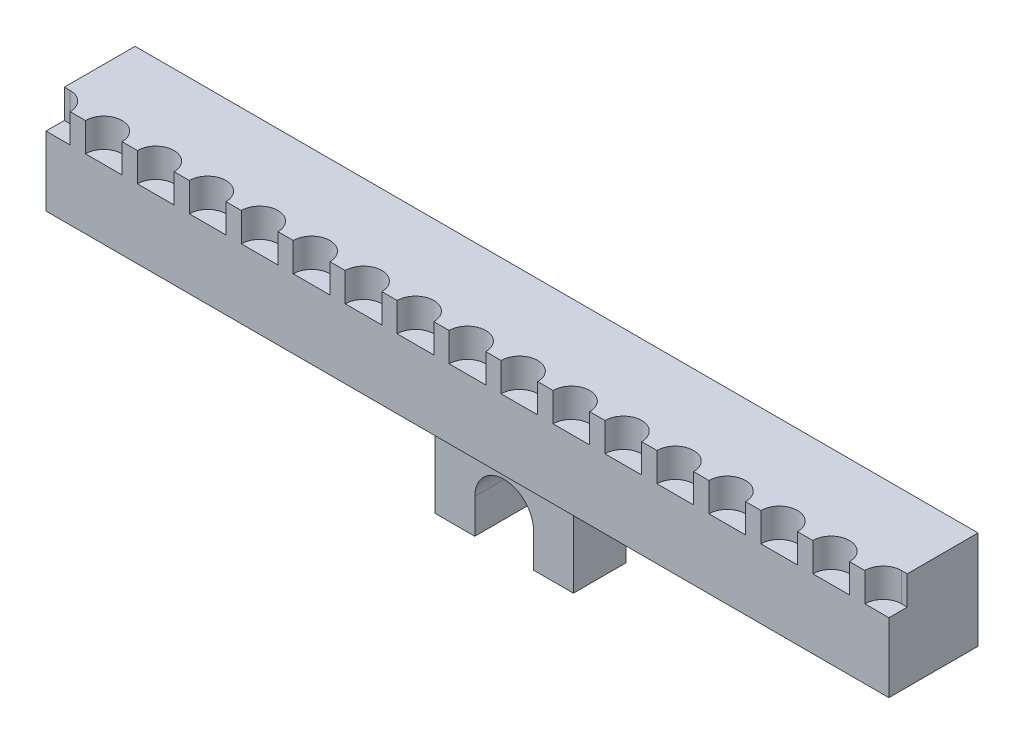
SolidWorks part; units mm, degrees
material "6061-T6 (SS)"
ref_plane "Front" through (0, 0, 0) normal (0, 0, 1) x (1, 0, 0)
ref_plane "Top" through (0, 0, 0) normal (0, 1, 0) x (1, 0, 0)
ref_plane "Right" through (0, 0, 0) normal (1, 0, 0) x (0, 0, -1)
sketch "Sketch1" plane through (0, 0, 0) normal (0, 1, 0) x (1, 0, 0)
  line L1 (-36.5, -7.215) -> (36.5, -7.215)
  line L2 (-36.5, -7.215) -> (-36.5, 0.5)
  line L3 (-36.5, 0.5) -> (36.5, 0.5)
  line L4 (36.5, -7.215) -> (36.5, 0.5)
  point P9 (0, 0.5)
  dimension "D1" = 7.715
  dimension "D2" = 73
  dimension "D3" = 0.5
extrude "Boss-Extrude1" add sketch "Sketch1" along normal blind 8.5
sketch "Sketch5" plane through (0, 0, 0) normal (0, 0, 1) x (1, 0, 0)
  line L0 (0, -4.8856) -> (0, -10.2239) construction
  line L1 (-2.54, -6) -> (-2.54, -9)
  line L2 (-6, 0) -> (6, 0)
  line L3 (-6, 0) -> (-6, -9)
  line L4 (-6, -9) -> (-2.54, -9)
  line L5 (6, 0) -> (6, -9)
  line L6 (2.54, -6) -> (2.54, -9)
  line L7 (2.54, -9) -> (6, -9)
  line L8 (-36.5, 0) -> (36.5, 0) construction
  arc A0 (2.54, -6) -> (-2.54, -6) centre (0, -6) ccw
  point P6 (0, 0)
  dimension "D3" = 5.08
  dimension "D1" = 12
  dimension "D2" = 9
  dimension "D4" = 6
extrude "Boss-Extrude5" add sketch "Sketch5" along normal up to surface and the other way up to surface up to face at (0, 4.25, 7.215) other way up to face at (0, 4.25, -0.5)
sketch "Sketch6" plane through (0, -9, 0) normal (0, -1, 0) x (1, 0, 0)
  line L0 (-6, 7.215) -> (-6, -0.5) construction
  line L1 (-6, 5.215) -> (6, 5.215)
  line L2 (-6, 5.215) -> (-6, 1.5)
  line L3 (-6, 1.5) -> (6, 1.5)
  line L4 (6, 5.215) -> (6, 1.5)
  line L5 (6, 7.215) -> (6, -0.5) construction
  line L6 (-2.54, 7.215) -> (-6, 7.215) construction
  line L7 (-2.54, -0.5) -> (-6, -0.5) construction
  dimension "D1" = 2
  dimension "D2" = 2
extrude "Cut-Extrude1" cut sketch "Sketch6" against normal up to surface (9 mm away) up to face at (-21.25, 0, 3.3575)
sketch "Sketch7" plane through (0, 8.5, 0) normal (0, 1, 0) x (1, 0, 0)
  line L0 (-36.5, -7.215) -> (36.5, -7.215) construction
  line L1 (0, -1.1644) -> (0, -11.0522) construction
  line L2 (36, -5.6275) -> (36.5, -5.6275)
  line L3 (36.5, -7.215) -> (36.5, 0.5) construction
  line L4 (36.5, -5.6275) -> (36.5, -5.7083)
  line L5 (-36.5, -5.6275) -> (-36.5, -5.7083)
  line L6 (-36, -5.6275) -> (-36.5, -5.6275)
  circle A0 centre (0, -7.215) radius 1.5875
  circle A2 centre (4.5, -7.215) radius 1.5875
  circle A3 centre (9, -7.215) radius 1.5875
  circle A4 centre (13.5, -7.215) radius 1.5875
  circle A5 centre (18, -7.215) radius 1.5875
  circle A6 centre (22.5, -7.215) radius 1.5875
  circle A7 centre (27, -7.215) radius 1.5875
  circle A8 centre (31.5, -7.215) radius 1.5875
  arc A9 (36, -5.6275) -> (36.5, -5.7083) centre (36, -7.215) ccw
  arc A10 (-36, -5.6275) -> (-36.5, -5.7083) centre (-36, -7.215) cw
  circle A11 centre (-31.5, -7.215) radius 1.5875
  circle A12 centre (-27, -7.215) radius 1.5875
  circle A13 centre (-22.5, -7.215) radius 1.5875
  circle A14 centre (-18, -7.215) radius 1.5875
  circle A15 centre (-13.5, -7.215) radius 1.5875
  circle A16 centre (-9, -7.215) radius 1.5875
  circle A17 centre (-4.5, -7.215) radius 1.5875
  dimension "D2" = 3.175
  dimension "D4" = 4.5
  dimension "D3" = 9
extrude "Cut-Extrude2" cut sketch "Sketch7" against normal blind 2.5
sketch "Sketch8" plane through (0, 0, 5.215) normal (0, 0, -1) x (-1, 0, 0)
  line L7 (2.54, -6) -> (2.54, -9)
  line L8 (2.54, -9) -> (6, -9)
  line L9 (6, -9) -> (6, 0)
  line L10 (6, 0) -> (-6, 0)
  line L11 (-6, 0) -> (-6, -9)
  line L12 (-6, -9) -> (-2.54, -9)
  line L13 (-2.54, -9) -> (-2.54, -6)
  line L14 (2.54, -6) -> (2.54, -9)
  line L15 (2.54, -9) -> (6, -9)
  line L16 (6, -9) -> (6, 0)
  line L17 (6, 0) -> (-6, 0)
  line L18 (-6, 0) -> (-6, -9)
  line L19 (-6, -9) -> (-2.54, -9)
  line L20 (-2.54, -9) -> (-2.54, -6)
  arc A1 (2.54, -6) -> (-2.54, -6) centre (0, -6) ccw
  arc A2 (2.54, -6) -> (-2.54, -6) centre (0, -6) ccw
  dimension "D1" = 0
extrude "Cut-Extrude3" cut sketch "Sketch8" against normal blind 2.54
sketch "Sketch9" plane through (0, 0, 1.5) normal (0, 0, 1) x (1, 0, 0)
  line L7 (2.54, -9) -> (6, -9)
  line L8 (6, -9) -> (6, 0)
  line L9 (6, 0) -> (-6, 0)
  line L10 (-6, 0) -> (-6, -9)
  line L11 (-6, -9) -> (-2.54, -9)
  line L12 (-2.54, -9) -> (-2.54, -6)
  line L13 (2.54, -6) -> (2.54, -9)
  line L14 (2.54, -9) -> (6, -9)
  line L15 (6, -9) -> (6, 0)
  line L16 (6, 0) -> (-6, 0)
  line L17 (-6, 0) -> (-6, -9)
  line L18 (-6, -9) -> (-2.54, -9)
  line L19 (-2.54, -9) -> (-2.54, -6)
  line L20 (2.54, -6) -> (2.54, -9)
  arc A1 (2.54, -6) -> (-2.54, -6) centre (0, -6) ccw
  arc A2 (2.54, -6) -> (-2.54, -6) centre (0, -6) ccw
  dimension "D1" = 0
extrude "Boss-Extrude6" add sketch "Sketch9" along normal blind 2.54
